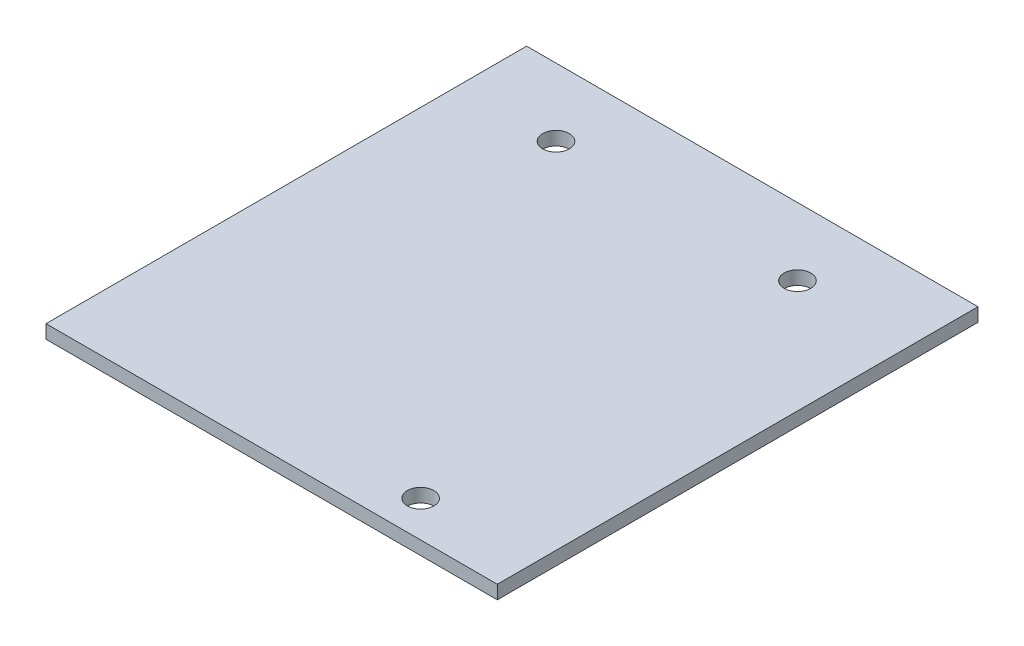
SolidWorks part; units mm, degrees
ref_plane "Front Plane" through (0, 0, 0) normal (0, 0, 1) x (1, 0, 0)
ref_plane "Top Plane" through (0, 0, 0) normal (0, 1, 0) x (1, 0, 0)
ref_plane "Right Plane" through (0, 0, 0) normal (1, 0, 0) x (0, 0, -1)
sketch "Sketch1" plane through (0, 0, 0) normal (0, 1, 0) x (1, 0, 0)
  line L1 (-25.4, 27.051) -> (25.4, 27.051)
  line L2 (-25.4, 27.051) -> (-25.4, -27.051)
  line L3 (-25.4, -27.051) -> (25.4, -27.051)
  line L4 (25.4, 27.051) -> (25.4, -27.051)
  line L5 (-25.4, 27.051) -> (25.4, -27.051) construction
  line L6 (-25.4, -27.051) -> (25.4, 27.051) construction
  point P0 (0, 0)
  dimension "D1" = 50.8
  dimension "D2" = 54.102
extrude "Boss-Extrude1" add sketch "Sketch1" along normal blind 1.524
sketch "Sketch2" plane through (0, 1.524, 0) normal (0, 1, 0) x (1, 0, 0)
  line L0 (-25.4, 27.051) -> (-25.4, -27.051) construction
  line L1 (25.4, 27.051) -> (-25.4, 27.051) construction
  circle A0 centre (-14.478, 19.431) radius 1.4986
  circle A1 centre (12.7, 19.431) radius 1.4986
  circle A2 centre (12.7, -22.987) radius 1.4986
  dimension "D1" = 2.9972
  dimension "D2" = 10.922
  dimension "D3" = 7.62
  dimension "D4" = 2.9972
  dimension "D5" = 27.178
  dimension "D6" = 42.418
  dimension "D7" = 2.9972
extrude "Cut-Extrude1" cut sketch "Sketch2" against normal blind 1.524
sketch "Sketch3" plane through (0, 1.524, 0) normal (0, 1, 0) x (1, 0, 0)
  line L0 (-14.478, 19.431) -> (12.7, 19.431)
  text T0 "      CounterCat" font "Century Gothic" height in points 8
